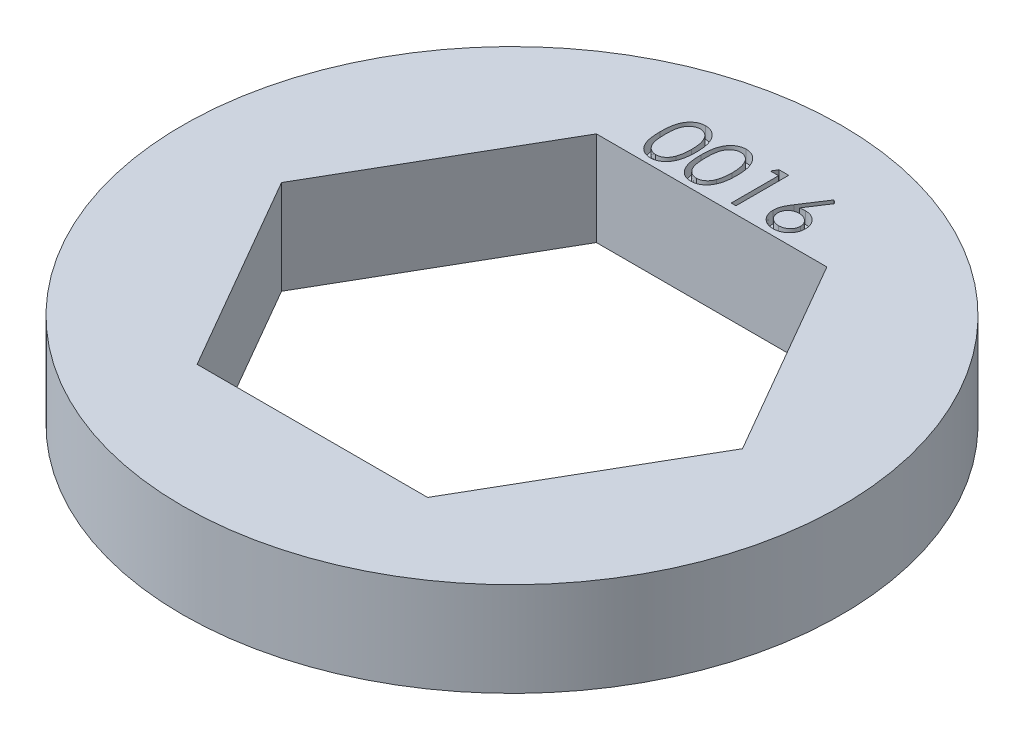
SolidWorks part; units mm, degrees
material "Nylon 101"
ref_plane "Front Plane" through (0, 0, 0) normal (0, 0, 1) x (1, 0, 0)
ref_plane "Top Plane" through (0, 0, 0) normal (0, 1, 0) x (1, 0, 0)
ref_plane "Right Plane" through (0, 0, 0) normal (1, 0, 0) x (0, 0, -1)
sketch "Sketch1" plane through (0, 0, 0) normal (0, 1, 0) x (1, 0, 0)
  line L1 (7.7723, 0) -> (3.8861, 6.731)
  line L2 (3.8861, 6.731) -> (-3.8861, 6.731)
  line L3 (-3.8861, 6.731) -> (-7.7723, 0)
  line L4 (-7.7723, 0) -> (-3.8861, -6.731)
  line L5 (-3.8861, -6.731) -> (3.8861, -6.731)
  line L6 (3.8861, -6.731) -> (7.7723, 0)
  circle A0 centre (0, 0) radius 11.1125
  circle A1 centre (0, 0) radius 6.731 construction
  dimension "D1" = 22.225
  dimension "D2" = 13.462
extrude "Boss-Extrude1" add sketch "Sketch1" along normal blind 3.175
sketch "Sketch2" plane through (0, 3.175, 0) normal (0, 1, 0) x (1, 0, 0)
  line L0 (-2.9431, 6.985) -> (2.8796, 6.985) construction
  line L1 (3.8861, 6.731) -> (-3.8861, 6.731) construction
  text T0 "0016" font "Century Gothic" height 1.778
  dimension "D1" = 0.254
extrude "Cut-Extrude1" cut sketch "Sketch2" against normal blind 0.4
